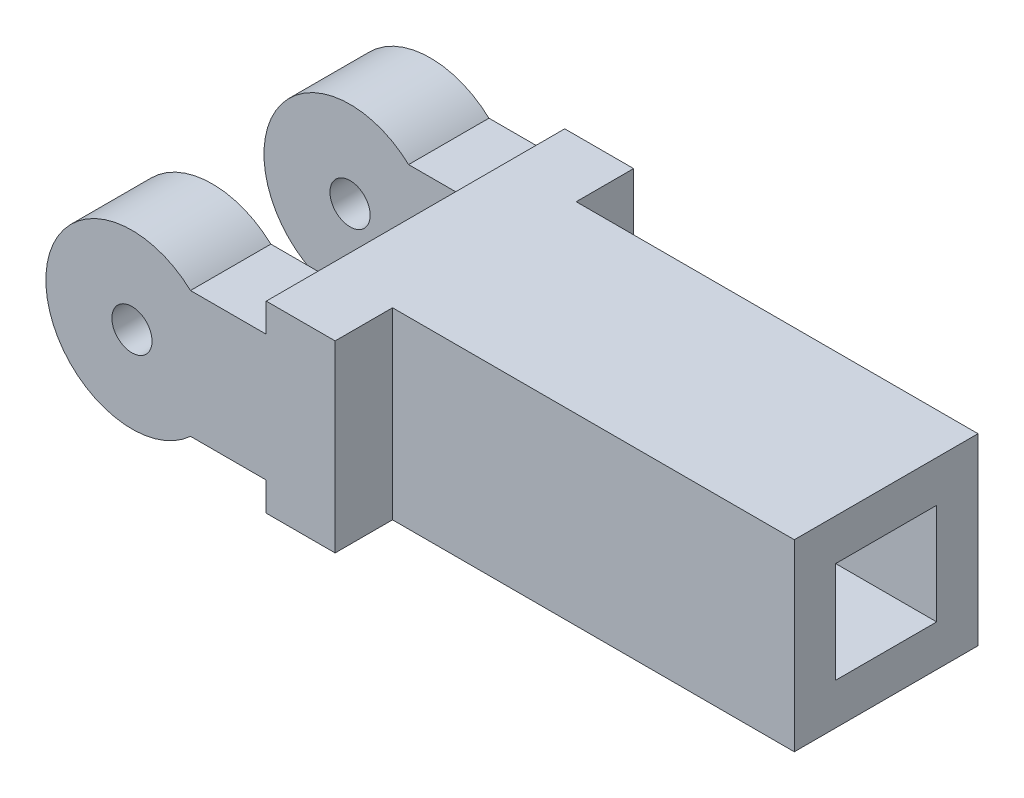
SolidWorks part; units mm, degrees
ref_plane "前视基准面" through (0, 0, 0) normal (0, 0, 1) x (1, 0, 0)
ref_plane "上视基准面" through (0, 0, 0) normal (0, 1, 0) x (1, 0, 0)
ref_plane "右视基准面" through (0, 0, 0) normal (1, 0, 0) x (0, 0, -1)
sketch "草图1" plane through (0, 0, 0) normal (1, 0, 0) x (0, 0, -1)
  line L1 (-1.6, -1.6) -> (1.6, -1.6)
  line L2 (-1.6, -1.6) -> (-1.6, 1.6)
  line L3 (-1.6, 1.6) -> (1.6, 1.6)
  line L4 (1.6, -1.6) -> (1.6, 1.6)
  line L5 (-1.6, -1.6) -> (1.6, 1.6) construction
  line L6 (-1.6, 1.6) -> (1.6, -1.6) construction
  line L7 (-0.88, -0.88) -> (0.88, -0.88)
  line L8 (-0.88, -0.88) -> (-0.88, 0.88)
  line L9 (-0.88, 0.88) -> (0.88, 0.88)
  line L10 (0.88, -0.88) -> (0.88, 0.88)
  line L11 (-0.88, -0.88) -> (0.88, 0.88) construction
  line L12 (-0.88, 0.88) -> (0.88, -0.88) construction
  point P0 (0, 0)
  point P6 (0, 0)
  dimension "D1" = 3.2
  dimension "D2" = 1.76
extrude "凸台-拉伸1" add sketch "草图1" along normal blind 7
sketch "草图2" plane through (0, 0, 0) normal (-1, 0, 0) x (0, 0, 1)
  line L4 (-1.6, 1.6) -> (-1.6, -1.6)
  line L5 (-1.6, -1.6) -> (1.6, -1.6)
  line L6 (1.6, -1.6) -> (1.6, 1.6)
  line L7 (1.6, 1.6) -> (-1.6, 1.6)
  line L8 (-1.6, 1.6) -> (-1.6, -1.6)
  line L9 (-1.6, -1.6) -> (1.6, -1.6)
  line L10 (1.6, -1.6) -> (1.6, 1.6)
  line L11 (1.6, 1.6) -> (-1.6, 1.6)
  dimension "D1" = 0
extrude "凸台-拉伸2" add sketch "草图2" along normal blind 1.2
sketch "草图3" plane through (0, 0, 0) normal (0, 0, 1) x (1, 0, 0)
  line L0 (-1.2, 0) -> (-3.5398, 0) construction
  line L1 (-1.2, 1.6) -> (-1.2, -1.6) construction
  line L2 (-1.2, 1.1) -> (-2.52, 1.1)
  line L3 (-1.2, 1.1) -> (-1.2, -1.1)
  line L4 (-1.2, -1.1) -> (-2.52, -1.1)
  line L5 (-2.52, 1.1) -> (-2.52, -1.1)
  line L6 (0, 0) -> (-1.2, 0) construction
  circle A0 centre (-3.5398, 0) radius 1.5
  dimension "D3" = 3
  dimension "D1" = 2.2
  dimension "D2" = 1.32
extrude "凸台-拉伸3" add sketch "草图3" against normal mid plane 5.2 contours A0 L4 L3 L2 | L5 A0 | L5 A0
sketch "草图4" plane through (0, 0, 0) normal (0, 0, 1) x (1, 0, 0)
  line L4 (-1.2, 1.1) -> (-2.52, 1.1)
  line L5 (-2.52, 1.1) -> (-2.52, -1.1)
  line L6 (-2.52, -1.1) -> (-1.2, -1.1)
  line L7 (-1.2, -1.1) -> (-1.2, 1.1)
  line L8 (-1.2, 1.1) -> (-2.52, 1.1)
  line L10 (-2.52, -1.1) -> (-1.2, -1.1)
  line L11 (-1.2, -1.1) -> (-1.2, 1.1)
  circle A1 centre (-3.5398, 0) radius 1.5
  arc A2 (-2.52, 1.1) -> (-2.52, -1.1) centre (-3.5398, 0) ccw
  dimension "D1" = 0
  dimension "D2" = 0
extrude "切除-拉伸1" cut sketch "草图4" against normal mid plane 2.4
sketch "草图5" plane through (-1.2, 0, 0) normal (1, 0, 0) x (0, 0, -1)
  line L0 (-1.6, 1.6) -> (1.6, 1.6) construction
  line L1 (-2.6, -1.6) -> (2.6, -1.6)
  line L2 (-2.6, -1.6) -> (-2.6, 1.6)
  line L3 (-2.6, 1.6) -> (2.6, 1.6)
  line L4 (2.6, -1.6) -> (2.6, 1.6)
  line L5 (-2.6, -1.6) -> (2.6, 1.6) construction
  line L6 (-2.6, 1.6) -> (2.6, -1.6) construction
  line L7 (2.6, 1.1) -> (2.6, -1.1) construction
  point P0 (0, 0)
extrude "凸台-拉伸4" add sketch "草图5" along normal blind 1.2
sketch "草图6" plane through (0, 0, 1.2) normal (0, 0, -1) x (-1, 0, 0)
  circle A0 centre (3.5398, 0) radius 0.35
  dimension "D1" = 0.7
extrude "切除-拉伸2" cut sketch "草图6" against normal through all both and the other way through all
